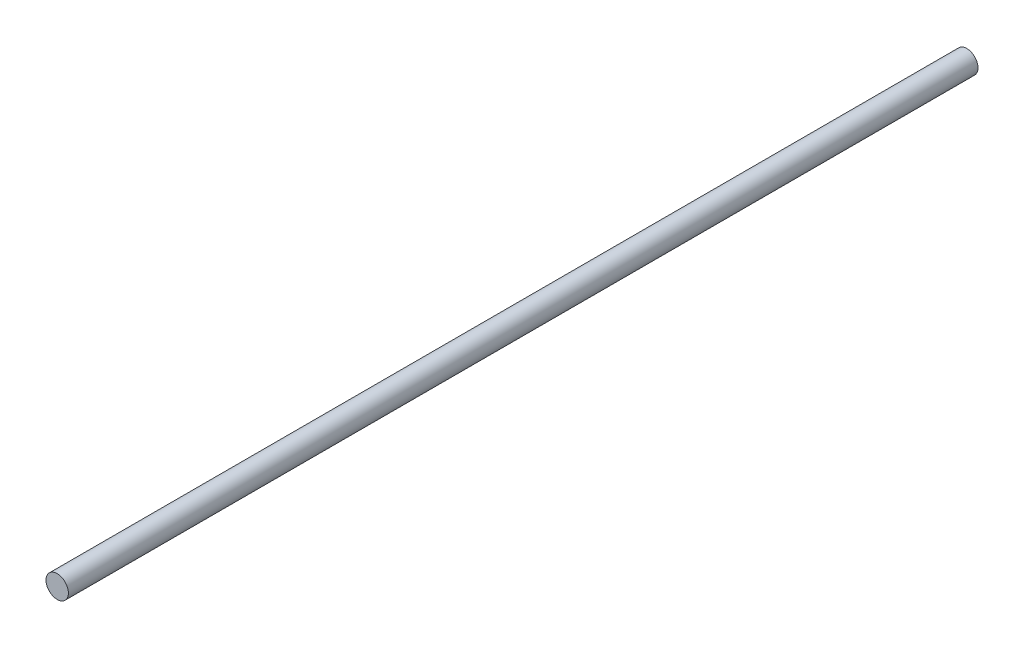
SolidWorks part; units mm, degrees
ref_plane "Front Plane" through (0, 0, 0) normal (0, 0, 1) x (1, 0, 0)
ref_plane "Top Plane" through (0, 0, 0) normal (0, 1, 0) x (1, 0, 0)
ref_plane "Right Plane" through (0, 0, 0) normal (1, 0, 0) x (0, 0, -1)
sketch "Sketch1" plane through (0, 0, 0) normal (0, 0, 1) x (1, 0, 0)
  circle A0 centre (16, 16) radius 16
  dimension "D1" = 32
extrude "Reference_only" add sketch "Sketch1" along normal blind 1300
